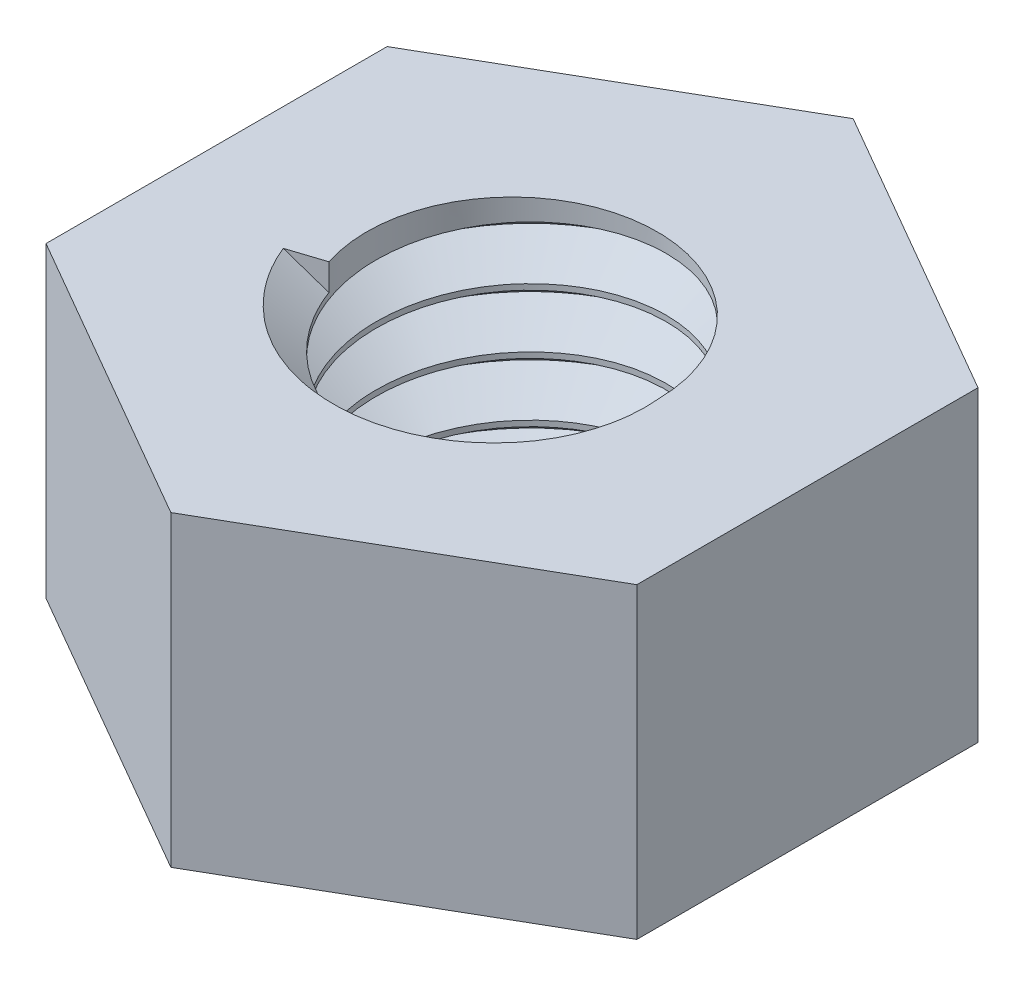
SolidWorks part; units mm, degrees
material "Acero aleado"
ref_plane "Alzado" through (0, 0, 0) normal (0, 0, 1) x (1, 0, 0)
ref_plane "Planta" through (0, 0, 0) normal (0, 1, 0) x (1, 0, 0)
ref_plane "Vista lateral" through (0, 0, 0) normal (1, 0, 0) x (0, 0, -1)
sketch "Sk_Hexagono" plane through (0, 0, 0) normal (0, 1, 0) x (1, 0, 0)
  line L0 (5, -2.8868) -> (0, -5.7735)
  line L1 (0, -5.7735) -> (-5, -2.8868)
  line L2 (-5, -2.8868) -> (-5, 2.8868)
  line L3 (-5, 2.8868) -> (0, 5.7735)
  line L4 (0, 5.7735) -> (5, 2.8868)
  line L5 (5, 2.8868) -> (5, -2.8868)
extrude "Hexagono" add sketch "Sk_Hexagono" along normal blind 5.2 from offset 0
sketch3d "Sk_Taladro"
  line L0 (0, -1, 0) -> (0, 6.2, 0)
  dimension "D1" = 7.2
sweep "Taladro" cut path "Sk_Taladro" circular profile diameter 4.9175 parameters "D3"=4.9175
sketch "Sk_Helice" plane through (0, 0, 0) normal (0, 1, 0) x (1, 0, 0)
  circle A0 centre (0, 0) radius 2.4587
curve "Helice_rosca" pitch 1 height 5.2 turns 5.2
sketch "Sk_Perfil_rosca" plane through (0, 0, 0) normal (1, 0, 0) x (0, 0, -1)
  line L0 (-2.2587, -0.6) -> (-3.0721, 0)
  line L1 (-3.0721, 0) -> (-2.2587, 0.6)
  line L2 (-2.2587, 0.6) -> (-2.2587, -0.6)
sweep "Rosca_M6x1,0" cut profiles "Sk_Perfil_rosca" path "Helice_rosca"
